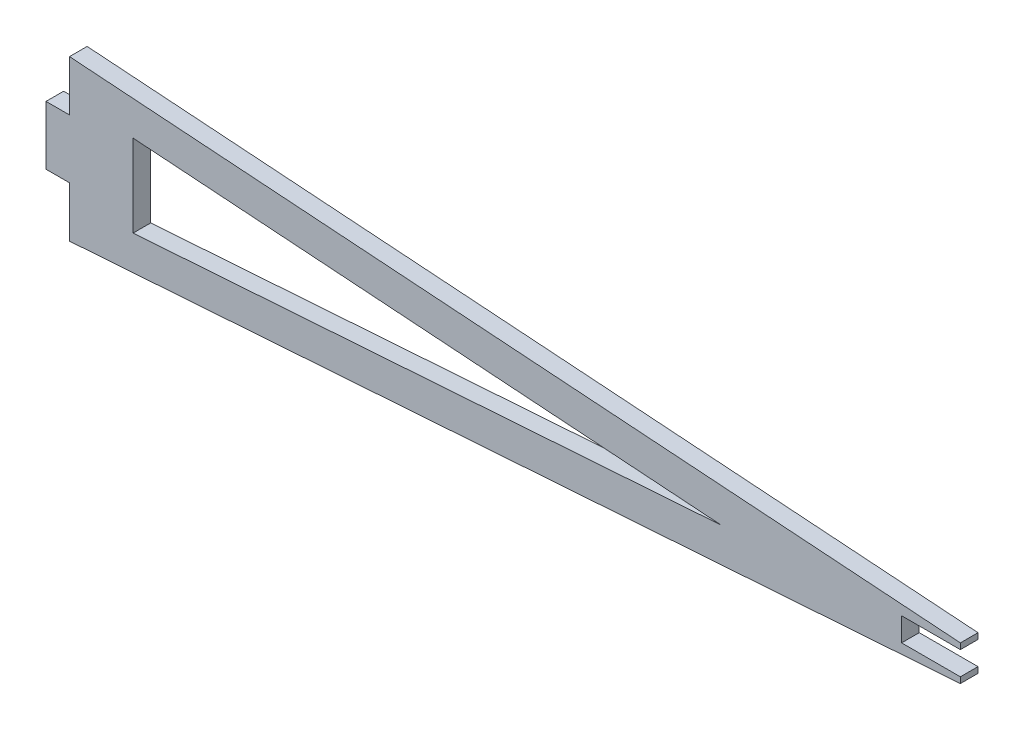
SolidWorks part; units mm, degrees
ref_plane "前视基准面" through (0, 0, 0) normal (0, 0, 1) x (1, 0, 0)
ref_plane "上视基准面" through (0, 0, 0) normal (0, 1, 0) x (1, 0, 0)
ref_plane "右视基准面" through (0, 0, 0) normal (1, 0, 0) x (0, 0, -1)
sketch "Model" plane through (0, 0, 0) normal (0, 0, 1) x (1, 0, 0)
  line L0 (18.4412, 12.001) -> (20.4419, 12.001)
  line L1 (20.4412, 17.001) -> (18.4412, 17.001)
  line L2 (18.4412, 17.001) -> (18.4412, 12.001)
  line L3 (20.4419, 7.701) -> (20.4419, 12.001)
  line L4 (20.4412, 17.001) -> (20.4419, 21.301)
  line L5 (20.4419, 21.301) -> (96.2354, 16.001)
  line L6 (20.4419, 7.701) -> (96.2354, 13.001)
  line L7 (96.2354, 13.001) -> (96.2354, 13.501)
  line L8 (96.2354, 15.501) -> (96.2354, 16.001)
  line L9 (25.8506, 11.001) -> (25.8506, 18.001)
  line L10 (25.8506, 11.001) -> (75.9029, 14.501)
  line L11 (25.8506, 18.001) -> (75.9029, 14.501)
  line L12 (96.2354, 15.501) -> (91.2354, 15.501)
  line L13 (96.2354, 13.501) -> (91.2354, 13.501)
  line L14 (91.2354, 15.501) -> (91.2354, 13.501)
extrude "凸台-拉伸1" add sketch "Model" along normal blind 1.5
